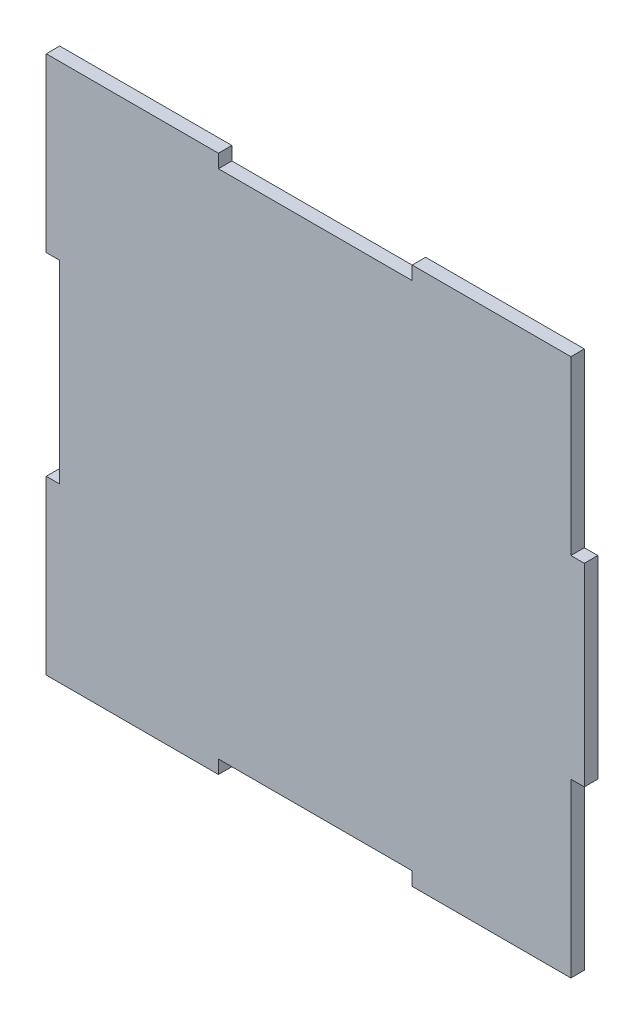
SolidWorks part; units mm, degrees
ref_plane "Front Plane" through (0, 0, 0) normal (0, 0, 1) x (1, 0, 0)
ref_plane "Top Plane" through (0, 0, 0) normal (0, 1, 0) x (1, 0, 0)
ref_plane "Right Plane" through (0, 0, 0) normal (1, 0, 0) x (0, 0, -1)
sketch "Sketch1" plane through (0, 0, 0) normal (0, 0, 1) x (1, 0, 0)
  line L0 (0, -100) -> (0, 100) construction
  line L1 (100, -100) -> (-100, -100) construction
  line L2 (100, -100) -> (100, 100) construction
  line L3 (100, 100) -> (-100, 100) construction
  line L4 (-100, -100) -> (-100, 100) construction
  line L5 (100, -100) -> (-100, 100) construction
  line L6 (100, 100) -> (-100, -100) construction
  line L7 (-100, 0) -> (100, 0) construction
  line L8 (36, 95) -> (-36, 95)
  line L9 (-36, 95) -> (-36, 100)
  line L10 (-36, 100) -> (-100, 100)
  line L11 (-100, 100) -> (-100, 36)
  line L12 (-100, 36) -> (-95, 36)
  line L13 (-95, 36) -> (-95, -36)
  line L14 (-95, -36) -> (-100, -36)
  line L15 (-100, -36) -> (-100, -100)
  line L16 (-100, -100) -> (-36, -100)
  line L17 (-36, -100) -> (-36, -95)
  line L18 (-36, -95) -> (36, -95)
  line L19 (36, -100) -> (36, -95)
  line L26 (36, 95) -> (36, 100)
  line L28 (36, 100) -> (95, 100)
  line L29 (95, 100) -> (95, 36)
  line L30 (95, 36) -> (100, 36)
  line L31 (100, 36) -> (100, -36)
  line L32 (100, -36) -> (95, -36)
  line L33 (95, -36) -> (95, -100)
  line L34 (95, -100) -> (36, -100)
  point P0 (0, 0)
  point P21 (0, -95)
  point P28 (0, 95)
  dimension "D1" = 200
  dimension "D2" = 200
  dimension "D3" = 72
  dimension "D4" = 5
  dimension "D6" = 5
  dimension "D7" = 5
  dimension "D9" = 5
  dimension "D10" = 5
extrude "Boss-Extrude1" add sketch "Sketch1" along normal blind 5
